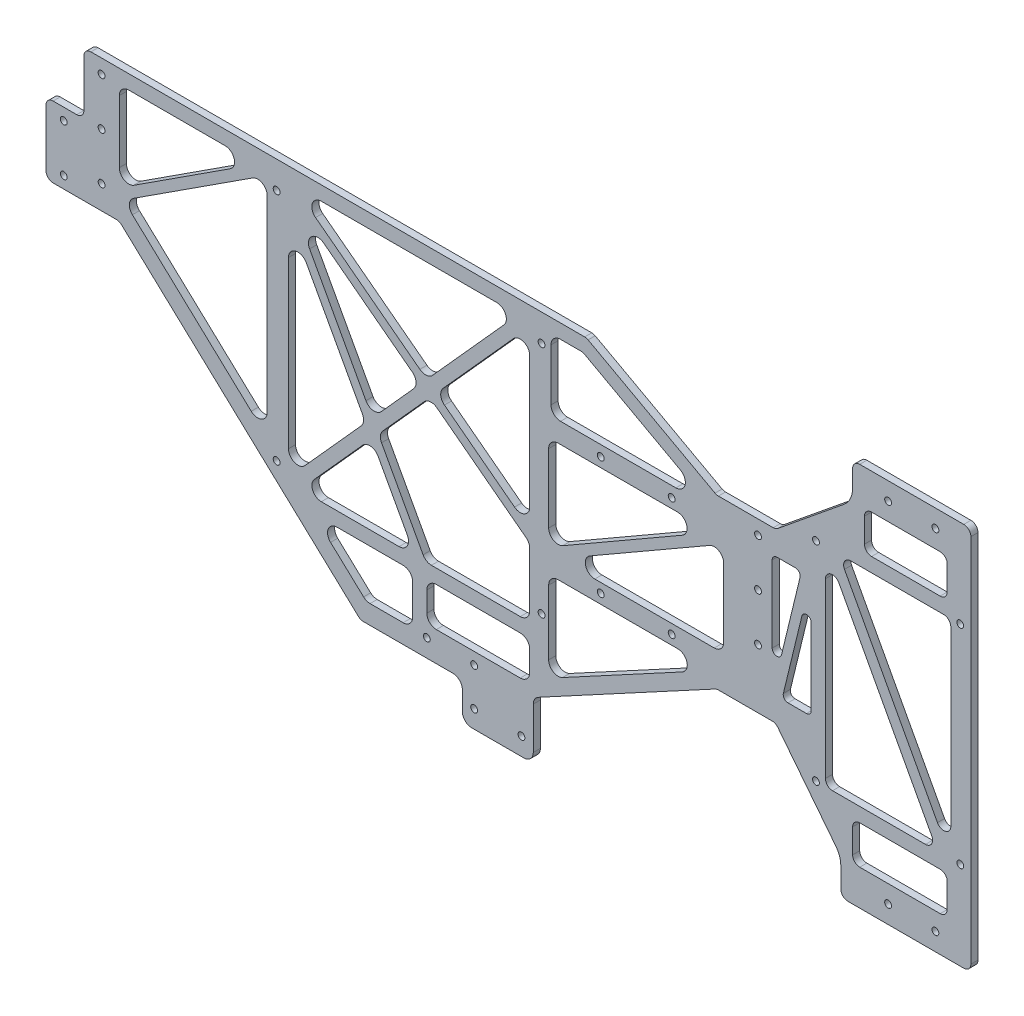
SolidWorks part; units mm, degrees
material "Thornel Mat VMA"
ref_plane "前视基准面" through (0, 0, 0) normal (0, 0, 1) x (1, 0, 0)
ref_plane "上视基准面" through (0, 0, 0) normal (0, 1, 0) x (1, 0, 0)
ref_plane "右视基准面" through (0, 0, 0) normal (1, 0, 0) x (0, 0, -1)
sketch "草图1" plane through (0, 0, 0) normal (0, 0, 1) x (1, 0, 0)
  line L0 (-285, 0) -> (-285, -237.5) construction
  line L1 (0, 0) -> (-292.5, 0) construction
  line L2 (0, 0) -> (0, -245) construction
  line L3 (0, -245) -> (-292.5, -245) construction
  line L4 (-292.5, 0) -> (-292.5, -245) construction
  line L5 (-285, -237.5) -> (-7.5, -237.5) construction
  line L6 (-7.5, -237.5) -> (-7.5, 0) construction
  line L10 (-292.5, -94) -> (-80, -94)
  line L11 (-80, -94) -> (-25, -124)
  line L12 (-25, -124) -> (0, -124)
  line L13 (-292.5, -94) -> (-292.5, -150)
  line L14 (-211, -204.5) -> (-99, -204.5) construction
  line L15 (-211, -204.5) -> (-211, -105.5) construction
  line L16 (-211, -105.5) -> (-99, -105.5) construction
  line L17 (-99, -204.5) -> (-99, -105.5) construction
  line L18 (-211, -204.5) -> (-99, -105.5) construction
  line L19 (-211, -105.5) -> (-99, -204.5) construction
  line L21 (-175.5, -245) -> (-117.5, -245)
  line L22 (-117.5, -245) -> (-25, -195)
  line L23 (-25, -195) -> (0, -195)
  line L25 (-292.5, -150) -> (-277.5, -150)
  line L26 (-277.5, -150) -> (-175.5, -245)
  line L27 (-277.5, -100) -> (-277.5, -139.7509)
  line L28 (-74, -184.5) -> (-44, -184.5) construction
  line L29 (-74, -184.5) -> (-74, -134.5) construction
  line L30 (-74, -134.5) -> (-44, -134.5) construction
  line L31 (-44, -184.5) -> (-44, -134.5) construction
  line L32 (-74, -184.5) -> (-44, -134.5) construction
  line L33 (-74, -134.5) -> (-44, -184.5) construction
  line L34 (-206, -210) -> (-104, -210)
  line L35 (-206, -210) -> (-206, -100)
  line L36 (-206, -100) -> (-104, -100)
  line L37 (-104, -210) -> (-104, -100)
  line L38 (-206, -210) -> (-104, -100) construction
  line L39 (-206, -100) -> (-104, -210) construction
  line L40 (-277.5, -139.7509) -> (-215, -197.9617)
  line L41 (-215, -197.9617) -> (-215, -100)
  line L42 (-215, -100) -> (-277.5, -100)
  line L43 (-95, -100) -> (-95, -130)
  line L44 (-96, -180.5) -> (-22, -180.5)
  line L45 (-96, -180.5) -> (-96, -138.5)
  line L46 (-96, -138.5) -> (-22, -138.5)
  line L47 (-22, -180.5) -> (-22, -138.5)
  line L48 (-96, -180.5) -> (-22, -138.5) construction
  line L49 (-96, -138.5) -> (-22, -180.5) construction
  line L50 (-95, -130) -> (-26.53, -130)
  line L51 (-26.53, -130) -> (-81.53, -100)
  line L52 (-81.53, -100) -> (-95, -100)
  line L53 (-195.6325, -216) -> (-153.5, -216)
  line L54 (-153.5, -216) -> (-153.5, -237)
  line L55 (-153.5, -237) -> (-173.0852, -237)
  line L56 (-173.0852, -237) -> (-195.6325, -216)
  line L57 (-96, -188.5) -> (-96, -226.5579)
  line L58 (-96, -226.5579) -> (-25.5928, -188.5)
  line L59 (-25.5928, -188.5) -> (-96, -188.5)
  line L60 (-147.5, -216) -> (-147.5, -232.5)
  line L61 (-147.5, -232.5) -> (-104, -232.5)
  line L62 (-104, -232.5) -> (-104, -216)
  line L63 (-104, -216) -> (-147.5, -216)
  line L65 (0, -124) -> (32.5, -97.5)
  line L66 (32.5, -97.5) -> (32.5, -82.5)
  line L67 (32.5, -82.5) -> (82.5, -82.5)
  line L68 (82.5, -82.5) -> (82.5, -245)
  line L69 (82.5, -245) -> (27.5, -245)
  line L72 (-7.5, -237.5) -> (82.5, -237.5) construction
  line L73 (82.5, -90) -> (32.5, -90) construction
  line L74 (0, -195) -> (27.5, -230)
  line L75 (27.5, -230) -> (27.5, -245)
  line L76 (82.5, -163.75) -> (0, -163.75) construction
  line L78 (17, -207.75) -> (78, -207.75) construction
  line L79 (17, -207.75) -> (17, -119.75) construction
  line L80 (17, -119.75) -> (78, -119.75) construction
  line L81 (78, -207.75) -> (78, -119.75) construction
  line L82 (17, -207.75) -> (78, -119.75) construction
  line L83 (17, -119.75) -> (78, -207.75) construction
  line L84 (21, -207.75) -> (74, -207.75)
  line L85 (21, -207.75) -> (21, -119.75)
  line L86 (21, -119.75) -> (74, -119.75)
  line L87 (74, -207.75) -> (74, -119.75)
  line L88 (21, -207.75) -> (74, -119.75) construction
  line L89 (21, -119.75) -> (74, -207.75) construction
  circle A0 centre (-285, -100) radius 1.45
  circle A1 centre (-285, -120) radius 1.45
  circle A2 centre (-285, -140) radius 1.45
  circle A3 centre (-147.5, -237.5) radius 1.45
  circle A4 centre (-127.5, -237.5) radius 1.45
  circle A5 centre (-7.5, -130) radius 1.45
  circle A6 centre (-7.5, -150) radius 1.45
  circle A7 centre (-211, -204.5) radius 1.45
  circle A8 centre (-211, -105.5) radius 1.45
  circle A9 centre (-99, -105.5) radius 1.45
  circle A10 centre (-99, -204.5) radius 1.45
  circle A11 centre (-74, -134.5) radius 1.45
  circle A12 centre (-44, -134.5) radius 1.45
  circle A13 centre (-74, -184.5) radius 1.45
  circle A14 centre (-44, -184.5) radius 1.45
  circle A15 centre (-7.5, -170) radius 1.45
  circle A16 centre (47.5, -90) radius 1.45
  circle A17 centre (67.5, -90) radius 1.45
  circle A18 centre (47.5, -237.5) radius 1.45
  circle A19 centre (67.5, -237.5) radius 1.45
  circle A20 centre (17, -119.75) radius 1.45
  circle A21 centre (78, -119.75) radius 1.45
  circle A22 centre (78, -207.75) radius 1.45
  circle A23 centre (17, -207.75) radius 1.45
  point P23 (-155, -155)
  point P36 (-59, -159.5)
  point P51 (-155, -155)
  point P58 (-59, -159.5)
  point P92 (57.5, -82.5)
  point P102 (47.5, -163.75)
  point P111 (47.5, -163.75)
  dimension "D6" = 2.9
  dimension "D7" = 20
  dimension "D8" = 20
  dimension "D9" = 100
  dimension "D10" = 20
  dimension "D12" = 20
  dimension "D13" = 120
  dimension "D14" = 6
  dimension "D15" = 6
  dimension "D18" = 2.9
  dimension "D23" = 2.9
  dimension "D28" = 10
  dimension "D30" = 28
  dimension "D50" = 20
  dimension "D57" = 2.9
  dimension "D60" = 20
  dimension "D65" = 2.9
  dimension "D66" = 20
  dimension "D67" = 47.5
  dimension "D71" = 2.9
  dimension "D72" = 4
  dimension "D1" = 292.5
  dimension "D2" = 245
  dimension "D3" = 7.5
  dimension "D4" = 7.5
  dimension "D5" = 7.5
  dimension "D11" = 130
  dimension "D16" = 80
  dimension "D17" = 25
  dimension "D19" = 99
  dimension "D20" = 112
  dimension "D21" = 155
  dimension "D22" = 90
  dimension "D24" = 30
  dimension "D25" = 50
  dimension "D26" = 40
  dimension "D27" = 45
  dimension "D29" = 15
  dimension "D31" = 10
  dimension "D32" = 50
  dimension "D33" = 25
  dimension "D34" = 6
  dimension "D35" = 5
  dimension "D36" = 7.5
  dimension "D37" = 8
  dimension "D38" = 6
  dimension "D39" = 6
  dimension "D40" = 4
  dimension "D41" = 6
  dimension "D42" = 7.5
  dimension "D43" = 6
  dimension "D44" = 4
  dimension "D45" = 6
  dimension "D46" = 4
  dimension "D47" = 8
  dimension "D48" = 6
  dimension "D49" = 4
  dimension "D51" = 6
  dimension "D52" = 6
  dimension "D53" = 5
  dimension "D54" = 8
  dimension "D55" = 162.5
  dimension "D56" = 7.5
  dimension "D58" = 90
  dimension "D59" = 50
  dimension "D61" = 47.5
  dimension "D62" = 15
  dimension "D63" = 15
  dimension "D64" = 55
  dimension "D68" = 61
  dimension "D69" = 88
  dimension "D70" = 35
extrude "凸台-拉伸1" add sketch "草图1" along normal blind 3
sketch "草图3" plane through (0, 0, 0) normal (0, 0, 1) x (1, 0, 0)
  line L0 (-206, -210) -> (-206, -208)
  line L1 (-206, -100) -> (-206, -210) construction
  line L2 (-206, -208) -> (-108.9253, -100)
  line L3 (-104, -100) -> (-206, -100) construction
  line L4 (-108.9253, -100) -> (-104, -100)
  line L5 (-104, -100) -> (-104, -102)
  line L6 (-104, -210) -> (-104, -100) construction
  line L7 (-104, -102) -> (-201.0747, -210)
  line L8 (-206, -210) -> (-104, -210) construction
  line L9 (-201.0747, -210) -> (-206, -210)
  line L10 (-277.5, -137.7509) -> (-219.2682, -100)
  line L11 (-277.5, -100) -> (-277.5, -139.7509) construction
  line L12 (-215, -100) -> (-277.5, -100) construction
  line L13 (-219.2682, -100) -> (-215, -100)
  line L14 (-215, -100) -> (-215, -102)
  line L15 (-215, -197.9617) -> (-215, -100) construction
  line L16 (-215, -102) -> (-275.7483, -141.3823)
  line L17 (-277.5, -139.7509) -> (-215, -197.9617) construction
  line L18 (-275.7483, -141.3823) -> (-277.5, -139.7509)
  line L19 (-277.5, -139.7509) -> (-277.5, -137.7509)
  line L20 (-22, -138.5) -> (-26.5423, -138.5)
  line L21 (-22, -138.5) -> (-96, -138.5) construction
  line L22 (-26.5423, -138.5) -> (-96, -178.5)
  line L23 (-96, -138.5) -> (-96, -180.5) construction
  line L24 (-96, -178.5) -> (-96, -180.5)
  line L25 (-96, -180.5) -> (-91.4577, -180.5)
  line L26 (-96, -180.5) -> (-22, -180.5) construction
  line L27 (-91.4577, -180.5) -> (-22, -140.5)
  line L28 (-22, -180.5) -> (-22, -138.5) construction
  line L29 (-22, -140.5) -> (-22, -138.5)
  dimension "D1" = 2
  dimension "D2" = 2
  dimension "D3" = 5
  dimension "D4" = 2
  dimension "D5" = 2
  dimension "D6" = 4
  dimension "D7" = 2
  dimension "D8" = 2
  dimension "D9" = 4
extrude "凸台-拉伸2" add sketch "草图3" along normal up to surface (3 mm away) up to face at (79.45, -207.75, 3)
sketch "草图4" plane through (0, 0, 0) normal (0, 0, 1) x (1, 0, 0)
  line L0 (-206, -100) -> (-204, -100)
  line L1 (-108.9253, -100) -> (-206, -100) construction
  line L2 (-204, -100) -> (-104, -176)
  line L3 (-104, -210) -> (-104, -102) construction
  line L4 (-104, -176) -> (-104, -181.0241)
  line L5 (-104, -181.0241) -> (-206, -103.5041)
  line L6 (-206, -100) -> (-206, -208) construction
  line L7 (-206, -103.5041) -> (-206, -100)
  line L8 (-147.9442, -210) -> (-206, -103.5041)
  line L9 (-201.0747, -210) -> (-104, -210) construction
  line L10 (-206, -111.8611) -> (-152.5, -210)
  line L11 (-152.5, -210) -> (-147.9442, -210)
  line L12 (-147.5, -216) -> (-147.5, -232.5) construction
  line L13 (-206, -111.8611) -> (-206, -103.5041)
  dimension "D1" = 2
  dimension "D2" = 4
  dimension "D3" = 76
  dimension "D4" = 4
  dimension "D5" = 5
extrude "凸台-拉伸3" add sketch "草图4" along normal up to surface (3 mm away) contours L7 L5 L4 L2 L0 | L13 L10 L11 L8 up to face at (-173.6418, -136, 3)
fillet "圆角1" radius 4 47 edges at (-91.4577, -180.5, 1.5) (-22, -180.5, 1.5) (-22, -140.5, 1.5) (-95, -130, 1.5) (-26.53, -130, 1.5) (-81.53, -100, 1.5) (-95, -100, 1.5) (-153.5, -237, 1.5) (-153.5, -216, 1.5) (-195.6325, -216, 1.5) (-173.0852, -237, 1.5) (-96, -226.5579, 1.5) (-25.5928, -188.5, 1.5) (-96, -188.5, 1.5) (-147.5, -232.5, 1.5) (-104, -232.5, 1.5) (-104, -216, 1.5) (-147.5, -216, 1.5) (-96, -138.5, 1.5) (-96, -178.5, 1.5) (-26.5423, -138.5, 1.5) (-215, -197.9617, 1.5) (-215, -102, 1.5) (-275.7483, -141.3823, 1.5) (-277.5, -137.7509, 1.5) (-219.2682, -100, 1.5) (-104, -102, 1.5) (-143.5184, -145.966, 1.5) (-104, -176, 1.5) (-147.5127, -142.9303, 1.5) (-108.9253, -100, 1.5) (-204, -100, 1.5) (-201.0747, -210, 1.5) (-152.5, -210, 1.5) (-170.8383, -176.3606, 1.5) (-104, -210, 1.5) (-104, -181.0241, 1.5) (-146.2014, -148.951, 1.5) (-168.0025, -173.2057, 1.5) (-147.9442, -210, 1.5) (-206, -111.8611, 1.5) (-206, -208, 1.5) (-173.3764, -171.7048, 1.5) (-170.5406, -168.5498, 1.5) (-150.1958, -145.9153, 1.5) (-206, -103.5041, 1.5) (-277.5, -100, 1.5)
sketch "草图6" plane through (0, 0, 3) normal (0, 0, 1) x (1, 0, 0)
  line L0 (21, -119.75) -> (21, -207.75) construction
  line L1 (37.5, -97.5) -> (72.5, -97.5)
  line L2 (37.5, -97.5) -> (37.5, -113.75)
  line L3 (37.5, -113.75) -> (72.5, -113.75)
  line L4 (72.5, -97.5) -> (72.5, -113.75)
  line L5 (32.5, -213.75) -> (72.5, -213.75)
  line L6 (32.5, -213.75) -> (32.5, -230)
  line L7 (32.5, -230) -> (72.5, -230)
  line L8 (72.5, -213.75) -> (72.5, -230)
  line L9 (-1.5, -134) -> (15, -134)
  line L10 (-1.5, -134) -> (-1.5, -185)
  line L11 (-1.5, -185) -> (15, -185)
  line L12 (15, -134) -> (15, -185)
  line L13 (0, -124) -> (-25, -124) construction
  line L14 (-25, -195) -> (0, -195) construction
  line L15 (74, -119.75) -> (21, -119.75) construction
  line L16 (82.5, -82.5) -> (32.5, -82.5) construction
  line L17 (32.5, -82.5) -> (32.5, -97.5) construction
  line L18 (82.5, -245) -> (82.5, -82.5) construction
  line L19 (21, -207.75) -> (74, -207.75) construction
  line L20 (27.5, -245) -> (82.5, -245) construction
  line L21 (27.5, -230) -> (27.5, -245) construction
  circle A0 centre (-7.5, -150) radius 1.45 construction
  dimension "D1" = 6
  dimension "D2" = 10
  dimension "D3" = 6
  dimension "D4" = 10
  dimension "D5" = 6
  dimension "D6" = 15
  dimension "D7" = 5
  dimension "D8" = 10
  dimension "D9" = 6
  dimension "D10" = 15
  dimension "D11" = 5
  dimension "D12" = 10
extrude "切除-拉伸1" cut sketch "草图6" against normal blind 3
sketch "草图7" plane through (0, 0, 0) normal (0, 0, 1) x (1, 0, 0)
  line L0 (21, -119.75) -> (68.3229, -207.75)
  line L1 (21, -207.75) -> (74, -207.75) construction
  line L2 (68.3229, -207.75) -> (74, -207.75)
  line L3 (74, -207.75) -> (26.6771, -119.75)
  line L4 (74, -119.75) -> (21, -119.75) construction
  line L5 (26.6771, -119.75) -> (21, -119.75)
  line L6 (15, -134) -> (10.8838, -134)
  line L7 (15, -134) -> (-1.5, -134) construction
  line L8 (10.8838, -134) -> (-1.5, -185)
  line L9 (-1.5, -185) -> (2.6162, -185)
  line L10 (-1.5, -185) -> (15, -185) construction
  line L11 (2.6162, -185) -> (15, -134)
  dimension "D1" = 4
  dimension "D2" = 5
extrude "凸台-拉伸4" add sketch "草图7" along normal blind 3
fillet "圆角2" radius 2 6 edges at (2.6162, -185, 1.5) (15, -134, 1.5) (15, -185, 1.5) (-1.5, -185, 1.5) (10.8838, -134, 1.5) (-1.5, -134, 1.5)
fillet "圆角3" radius 3 14 edges at (72.5, -213.75, 1.5) (72.5, -230, 1.5) (32.5, -230, 1.5) (32.5, -213.75, 1.5) (72.5, -113.75, 1.5) (37.5, -113.75, 1.5) (37.5, -97.5, 1.5) (72.5, -97.5, 1.5) (26.6771, -119.75, 1.5) (74, -207.75, 1.5) (74, -119.75, 1.5) (68.3229, -207.75, 1.5) (21, -119.75, 1.5) (21, -207.75, 1.5)
fillet "圆角4" radius 10 2 edges at (27.5, -230, 1.5) (32.5, -97.5, 1.5)
sketch "草图8" plane through (0, 0, 0) normal (0, 0, 1) x (1, 0, 0)
  line L0 (-292.5, -150) -> (-308.5, -150)
  line L1 (-308.5, -150) -> (-308.5, -120)
  line L2 (-308.5, -120) -> (-292.5, -120)
  line L3 (-292.5, -94) -> (-292.5, -150) construction
  line L4 (-292.5, -120) -> (-292.5, -150)
  line L5 (-301, -120) -> (-301, -150) construction
  circle A0 centre (-285, -120) radius 1.45 construction
  circle A1 centre (-301, -145) radius 1.45
  circle A2 centre (-301, -125) radius 1.45
  dimension "D4" = 2.9
  dimension "D5" = 20
  dimension "D6" = 5
  dimension "D1" = 16
  dimension "D2" = 7.5
  dimension "D3" = 30
extrude "凸台-拉伸5" add sketch "草图8" along normal blind 3
fillet "圆角5" radius 3 16 edges at (-292.5, -94, 1.5) (-80, -94, 1.5) (-25, -124, 1.5) (0, -124, 1.5) (32.5, -82.5, 1.5) (82.5, -82.5, 1.5) (82.5, -245, 1.5) (27.5, -245, 1.5) (0, -195, 1.5) (-25, -195, 1.5) (-117.5, -245, 1.5) (-175.5, -245, 1.5) (-277.5, -150, 1.5) (-308.5, -120, 1.5) (-292.5, -120, 1.5) (-308.5, -150, 1.5)
sketch "草图9" plane through (0, 0, 0) normal (0, 0, 1) x (1, 0, 0)
  line L0 (-132.5, -245) -> (-122.5, -245)
  line L1 (-174.3193, -245) -> (-118.2589, -245) construction
  line L2 (-122.5, -245) -> (-102.5, -236.8919)
  line L3 (-116.8324, -244.6391) -> (-25.6676, -195.3609) construction
  line L4 (-102.5, -236.8919) -> (-102.5, -261)
  line L5 (-102.5, -261) -> (-132.5, -261)
  line L6 (-132.5, -261) -> (-132.5, -245)
  line L7 (-127.5, -253.5) -> (-107.5, -253.5) construction
  line L8 (-127.5, -237.5) -> (-127.5, -253.5) construction
  circle A0 centre (-127.5, -237.5) radius 1.45 construction
  circle A1 centre (-127.5, -253.5) radius 1.45
  circle A2 centre (-107.5, -253.5) radius 1.45
  dimension "D2" = 5
  dimension "D4" = 2.9
  dimension "D1" = 5
  dimension "D3" = 30
  dimension "D5" = 7.5
  dimension "D6" = 16
  dimension "D7" = 20
extrude "凸台-拉伸6" add sketch "草图9" along normal up to surface (3 mm away) up to face at (36.995, -180.776, 3)
fillet "圆角6" radius 4 4 edges at (-102.5, -261, 1.5) (-132.5, -261, 1.5) (-102.5, -236.8919, 1.5) (-132.5, -245, 1.5)
